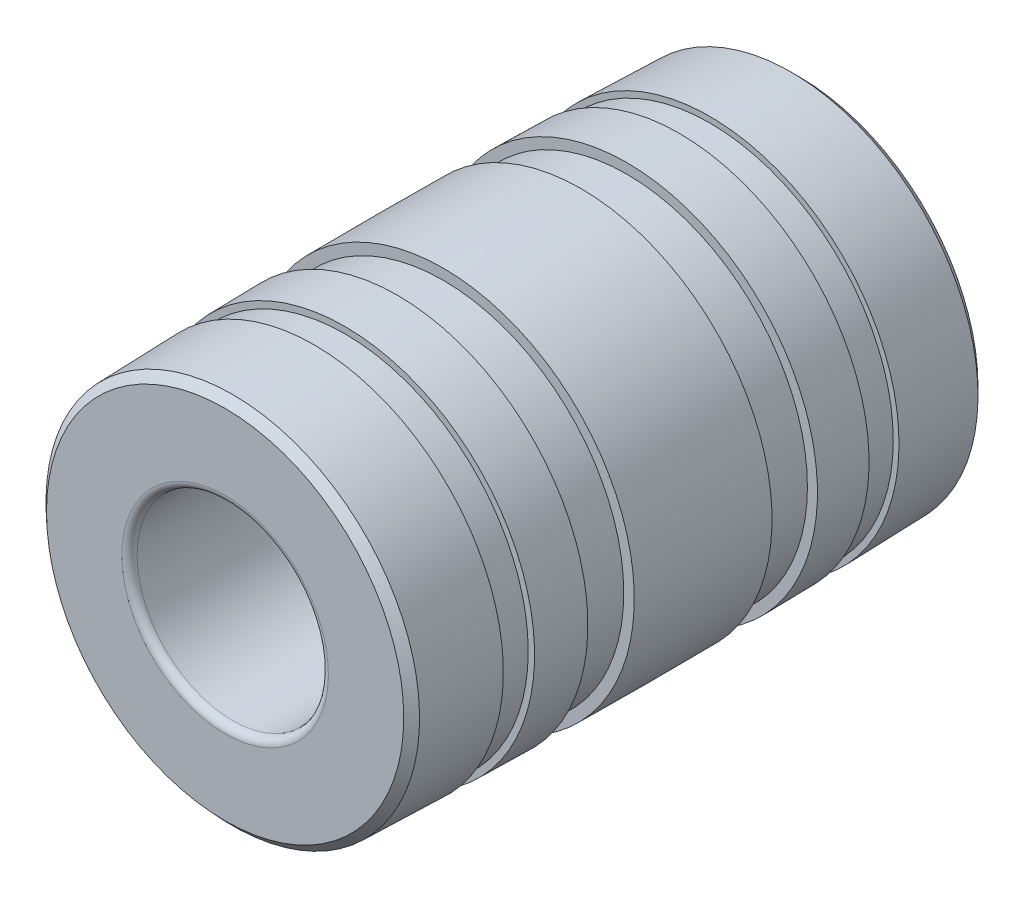
SolidWorks part; units mm, degrees
ref_plane "Front" through (0, 0, 0) normal (0, 0, 1) x (1, 0, 0)
ref_plane "Top" through (0, 0, 0) normal (0, 1, 0) x (1, 0, 0)
ref_plane "Right" through (0, 0, 0) normal (1, 0, 0) x (0, 0, -1)
sketch "Sketch1" plane through (0, 0, 0) normal (1, 0, 0) x (0, 0, -1)
  line L0 (-9.525, 0) -> (9.525, 0)
  line L1 (-9.525, 0) -> (-9.525, -6.1912)
  line L2 (0, 0) -> (0, -6.35) construction
  line L3 (-9.525, -6.1912) -> (-9.525, 6.1913) construction
  line L4 (-6.5659, -6.2746) -> (-6.5659, -6.0841)
  line L5 (-6.5659, -6.0841) -> (-5.5499, -6.0841)
  line L6 (-5.5499, -6.0841) -> (-5.5499, -6.2961)
  line L7 (-9.525, -6.35) -> (-9.525, 6.35) construction
  line L8 (6.5659, -6.0841) -> (9.525, -6.0841) construction
  line L9 (9.525, -6.0841) -> (9.525, 6.0841) construction
  line L10 (9.525, 0) -> (9.525, -6.1912)
  line L11 (-5.5499, -6.35) -> (5.5499, -6.35) construction
  line L12 (-3.81, -6.3246) -> (-3.81, -5.9912)
  line L13 (-3.81, -5.9912) -> (-2.286, -5.9912)
  line L14 (-2.286, -5.9912) -> (-2.286, -6.3409)
  line L15 (-2.286, -5.9912) -> (0, -5.9912) construction
  line L16 (5.5499, -6.0841) -> (5.5499, -6.2961)
  line L17 (6.5659, -6.0841) -> (5.5499, -6.0841)
  line L18 (6.5659, -6.2746) -> (6.5659, -6.0841)
  line L19 (0, -5.9912) -> (2.286, -5.9912) construction
  line L20 (-5.5499, -6.0841) -> (-3.81, -6.0841) construction
  line L21 (5.5499, -6.0841) -> (3.81, -6.0841) construction
  line L22 (2.286, -6.3409) -> (2.286, -5.9912)
  line L23 (2.286, -5.9912) -> (3.81, -5.9912)
  line L24 (3.81, -5.9912) -> (3.81, -6.3246)
  line L25 (-6.5659, -6.2746) -> (6.5659, -6.2746) construction
  arc A0 (0, -6.35) -> (-2.286, -6.3409) centre (0, 279.4794) cw
  arc A1 (0, -6.35) -> (2.286, -6.3409) centre (0, 279.4794) ccw
  arc A2 (-3.81, -6.3246) -> (-5.5499, -6.2961) centre (0, 279.4794) cw
  arc A3 (-6.5659, -6.2746) -> (-9.525, -6.1912) centre (0, 279.4794) cw
  arc A4 (3.81, -6.3246) -> (5.5499, -6.2961) centre (0, 279.4794) ccw
  arc A5 (6.5659, -6.2746) -> (9.525, -6.1912) centre (0, 279.4794) ccw
  point P13 (9.525, 6.35)
  dimension "D1" = 1.524
  dimension "D4" = 12.3825
  dimension "D2" = 0.1905
  dimension "D3" = 0.3334
  dimension "D5" = 1.016
revolve "Bearing" add sketch "Sketch1" angle 360 mid plane about L0
sketch "Sketch2" plane through (0, 0, 0) normal (0, 0, 1) x (1, 0, 0)
  circle A0 centre (0, 0) radius 3.175
  circle A1 centre (0, 0) radius 6.35 construction
  dimension "For Shaft Dia" = 6.35
extrude "Bore" cut sketch "Sketch2" against normal through all and the other way through all
chamfer "OD Chamfer" distance 0.254 angle 45 2 edges at (0, -6.1913, -9.525) (0, -6.1912, 9.525)
fillet "ID Fillet" radius 0.254 2 edges at (3.175, 0, -9.525) (3.175, 0, 9.525)
sketch "Retaining Hole" [suppressed] plane through (0, 0, 0) normal (1, 0, 0) x (0, 0, -1)
  line L0 (-9.525, -6.1912) -> (-9.525, 6.1913) construction
  line L1 (-9.525, 0) -> (9.525, 0) construction
  circle A0 centre (0, 0) radius 1.1938
  dimension "Supplier H Hole Dia" = 2.3876
  dimension "Supplier I Hole Locate" = 9.525
extrude "Retaining Hole " [suppressed] cut sketch "Retaining Hole" along normal through all
sketch "Slot Opening" [suppressed] plane through (0, 0, 0) normal (0, 0, 1) x (1, 0, 0)
  line L0 (0, -38.1) -> (0, -3.2029) construction
  line L1 (-12.7, -21.997) -> (12.7, -21.997)
  line L2 (-12.7, -21.997) -> (-21.997, -38.1)
  line L3 (-21.997, -38.1) -> (21.997, -38.1)
  line L4 (21.997, -38.1) -> (12.7, -21.997)
  circle A2 centre (0, 0) radius 25.4 construction
  dimension "D1" = 60
  dimension "Wd E" = 3.175
extrude "Slot Opening " [suppressed] cut sketch "Slot Opening" against normal through all and the other way through all
other "Move Face1" [suppressed] parameters "D1"=3.175
other "Move Face2" [suppressed] parameters "D1"=15
sketch "Ref" [suppressed] plane through (0, 0, 0) normal (0, 0, 1) x (1, 0, 0)
  line L0 (13.0254, 5.2388) -> (7.0543, 3.6389) construction
  line L1 (13.2667, 5.3035) -> (7.0543, 3.6389) construction
  line L2 (7.9286, 0.3758) -> (13.8998, 1.9757) construction
  line L3 (7.9286, 0.3758) -> (14.1411, 2.0404) construction
  line L4 (7.667, 2.0544) -> (13.8007, 3.6979) construction
  line L5 (0, 0) -> (14.2875, 0) construction
  circle A0 centre (0, 0) radius 14.2875 construction
  arc A1 (14.1411, 2.0404) -> (13.2667, 5.3035) centre (0, 0) ccw construction
  circle A2 centre (0, 0) radius 7.9375 construction
  arc A3 (7.9286, 0.3758) -> (7.0543, 3.6389) centre (0, 0) ccw construction
equation "\"D1@Sketch1\" = \"D5@Sketch1\" * 1.5"
equation "\"D4@Sketch1\" = \"OD A@Sketch1\" * .975"
equation "\"D2@Sketch1\" = \"OD A@Sketch1\" * .015"
equation "\"D3@Sketch1\" = \"D2@Sketch1\" * 1.75"
